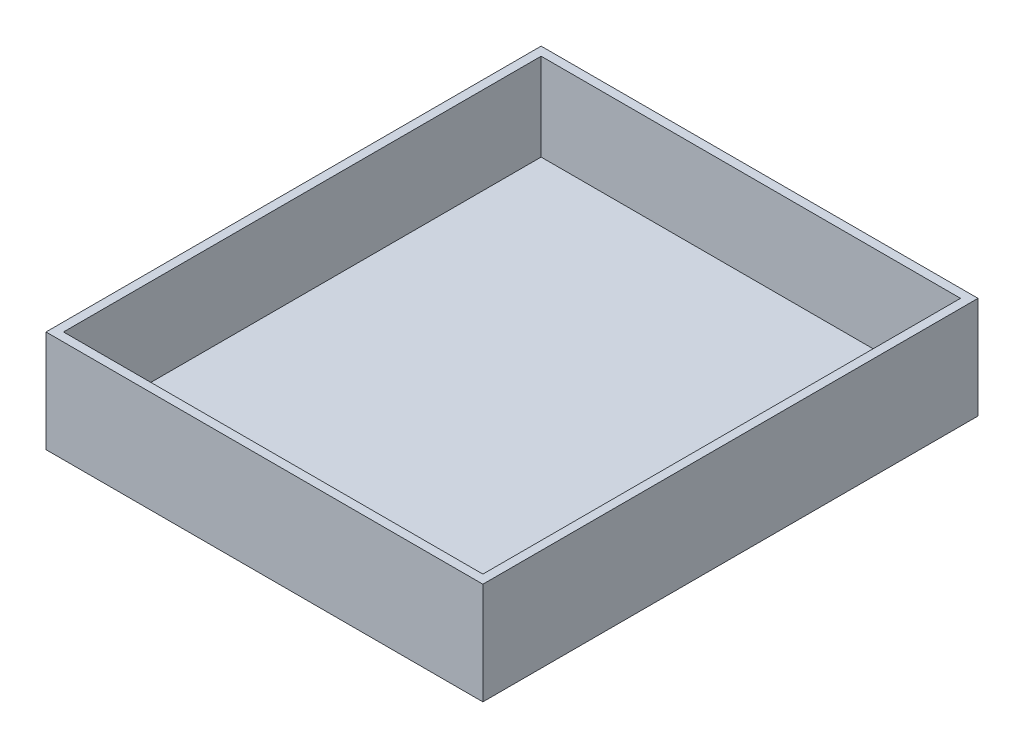
SolidWorks part; units mm, degrees
ref_plane "Front Plane" through (0, 0, 0) normal (0, 0, 1) x (1, 0, 0)
ref_plane "Top Plane" through (0, 0, 0) normal (0, 1, 0) x (1, 0, 0)
ref_plane "Right Plane" through (0, 0, 0) normal (1, 0, 0) x (0, 0, -1)
sketch "Sketch1" plane through (0, 0, 0) normal (0, 1, 0) x (1, 0, 0)
  line L1 (-75, -85) -> (75, -85)
  line L2 (-75, -85) -> (-75, 85)
  line L3 (-75, 85) -> (75, 85)
  line L4 (75, -85) -> (75, 85)
  line L5 (-75, -85) -> (75, 85) construction
  line L6 (-75, 85) -> (75, -85) construction
  point P0 (0, 0)
  dimension "D1" = 150
  dimension "D2" = 170
extrude "Boss-Extrude1" add sketch "Sketch1" along normal blind 5
sketch "Sketch3" plane through (0, 5, 0) normal (0, 1, 0) x (1, 0, 0)
  line L0 (-72, -82) -> (-72, 82)
  line L1 (-75, -85) -> (75, -85)
  line L2 (-75, -85) -> (-75, 85)
  line L3 (-75, 85) -> (75, 85)
  line L4 (75, -85) -> (75, 85)
  line L5 (-72, 82) -> (72, 82)
  line L6 (72, -82) -> (72, 82)
  line L7 (-72, -82) -> (72, -82)
  point P1 (0, 0)
  dimension "D1" = 3
extrude "Boss-Extrude3" add sketch "Sketch3" along normal blind 30
